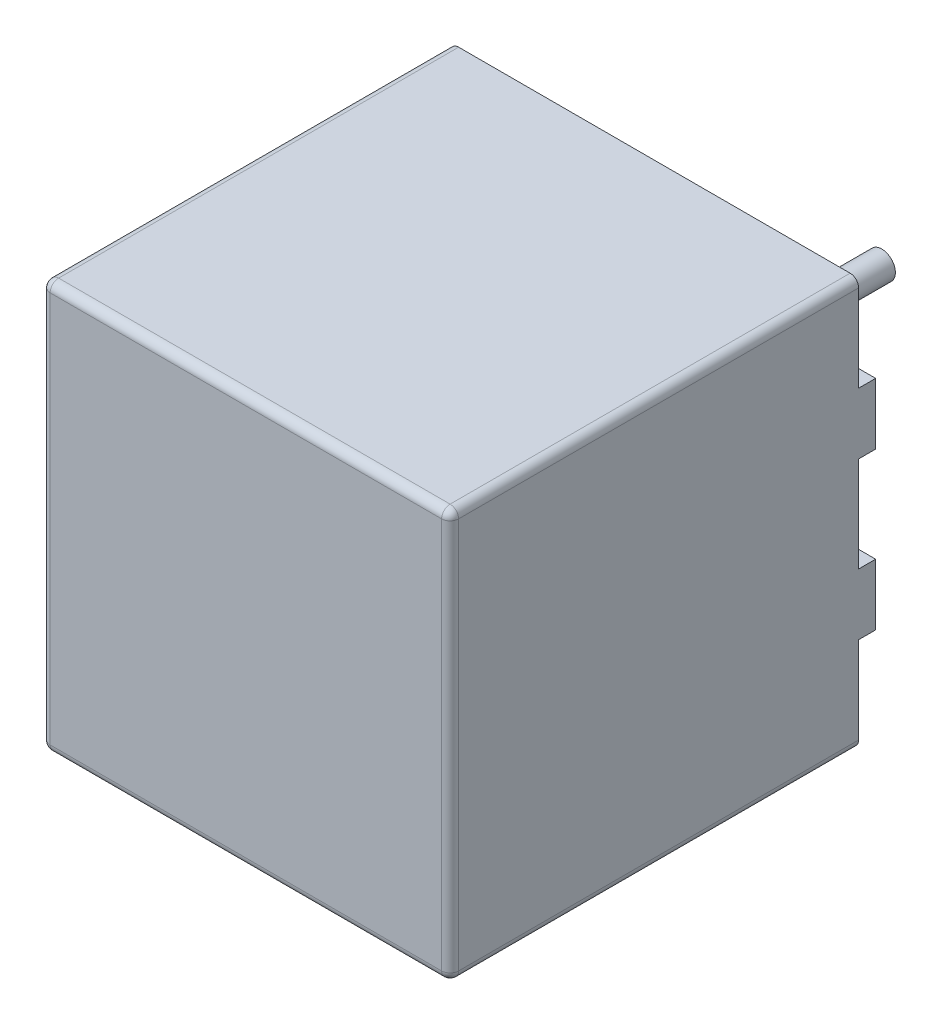
SolidWorks part; units mm, degrees
ref_plane "Front Plane" through (0, 0, 0) normal (0, 0, 1) x (1, 0, 0)
ref_plane "Top Plane" through (0, 0, 0) normal (0, 1, 0) x (1, 0, 0)
ref_plane "Right Plane" through (0, 0, 0) normal (1, 0, 0) x (0, 0, -1)
sketch "Sketch1" plane through (0, 0, 0) normal (0, 0, 1) x (1, 0, 0)
  line L1 (-5.75, 6) -> (5.75, 6)
  line L2 (-6, 5.75) -> (-6, -5.75)
  line L3 (-5.75, -6) -> (5.75, -6)
  line L4 (6, 5.75) -> (6, -5.75)
  line L5 (-6, 6) -> (6, -6) construction
  line L6 (-6, -6) -> (6, 6) construction
  arc A0 (-6, -5.75) -> (-5.75, -6) centre (-5.75, -5.75) ccw
  arc A1 (5.75, -6) -> (6, -5.75) centre (5.75, -5.75) ccw
  arc A2 (5.75, 6) -> (6, 5.75) centre (5.75, 5.75) cw
  arc A3 (-5.75, 6) -> (-6, 5.75) centre (-5.75, 5.75) ccw
  point P0 (0, 0)
  dimension "D2" = 0.25
  dimension "D1" = 12
extrude "Boss-Extrude1" add sketch "Sketch1" along normal blind 12.5
sketch "Sketch2" plane through (0, 0, 0) normal (0, 0, -1) x (-1, 0, 0)
  line L0 (-6, -5.75) -> (-6, 5.75) construction
  line L1 (5.25, -5.5) -> (-5.25, -5.5)
  line L2 (5.5, -5.25) -> (5.5, 5.25)
  line L3 (5.25, 5.5) -> (-5.25, 5.5)
  line L4 (-5.5, -5.25) -> (-5.5, 5.25)
  line L5 (5.5, -5.5) -> (-5.5, 5.5) construction
  line L6 (5.5, 5.5) -> (-5.5, -5.5) construction
  arc A0 (5.25, -5.5) -> (5.5, -5.25) centre (5.25, -5.25) ccw
  arc A1 (-5.25, -5.5) -> (-5.5, -5.25) centre (-5.25, -5.25) cw
  arc A2 (5.5, 5.25) -> (5.25, 5.5) centre (5.25, 5.25) ccw
  arc A3 (-5.25, 5.5) -> (-5.5, 5.25) centre (-5.25, 5.25) ccw
  point P0 (0, 0)
  dimension "D2" = 0.25
  dimension "D1" = 0.5
extrude "Cut-Extrude1" cut sketch "Sketch2" against normal blind 1
sketch "Sketch3" plane through (6, 0, 0) normal (1, 0, 0) x (0, 0, -1)
  line L0 (0, -5.75) -> (0, 5.75) construction
  line L1 (0, -1.4) -> (-0.5, -1.4)
  line L2 (0, -1.4) -> (0, 1.4)
  line L3 (0, 1.4) -> (-0.5, 1.4)
  line L4 (-0.5, -1.4) -> (-0.5, 1.4)
  line L5 (-12.5, -6) -> (0, -6) construction
  line L6 (0, 6) -> (-0.5, 6)
  line L7 (0, 6) -> (0, 3.2)
  line L8 (0, 3.2) -> (-0.5, 3.2)
  line L9 (-0.5, 6) -> (-0.5, 3.2)
  line L10 (0, -6) -> (-0.5, -6)
  line L11 (0, -6) -> (0, -3.2)
  line L12 (0, -3.2) -> (-0.5, -3.2)
  line L13 (-0.5, -6) -> (-0.5, -3.2)
  line L14 (-12.5, 6) -> (0, 6) construction
  point P16 (0, 0)
  dimension "D1" = 0.5
  dimension "D2" = 1.8
  dimension "D3" = 2.8
extrude "Cut-Extrude2" cut sketch "Sketch3" against normal blind 20
fillet "Fillet1" radius 0.25 8 edges at (0, -5.5, 1) (5.4268, -5.4268, 1) (5.5, 0, 1) (5.4268, 5.4268, 1) (0, 5.5, 1) (-5.4268, 5.4268, 1) (-5.5, 0, 1) (-5.4268, -5.4268, 1)
fillet "Fillet2" radius 0.25 8 edges at (-6, 0, 12.5) (-5.9268, 5.9268, 12.5) (0, 6, 12.5) (5.9268, 5.9268, 12.5) (6, 0, 12.5) (5.9268, -5.9268, 12.5) (0, -6, 12.5) (-5.9268, -5.9268, 12.5)
sketch "Sketch4" plane through (0, 0, 1) normal (0, 0, -1) x (-1, 0, 0)
  line L0 (-5.08, 5.08) -> (5.08, -5.08) construction
  line L1 (-5.25, 0) -> (5.25, 0) construction
  line L2 (-5.25, 5.25) -> (-5.25, -5.25) construction
  line L3 (5.25, -5.25) -> (5.25, 5.25) construction
  circle A0 centre (-5.08, 5.08) radius 0.4
  circle A1 centre (5.08, -5.08) radius 0.4
  point P3 (0, 0)
  dimension "D3" = 0.8
  dimension "D1" = 135
  dimension "D2" = 5.08
extrude "Boss-Extrude2" add sketch "Sketch4" along normal blind 2.1
